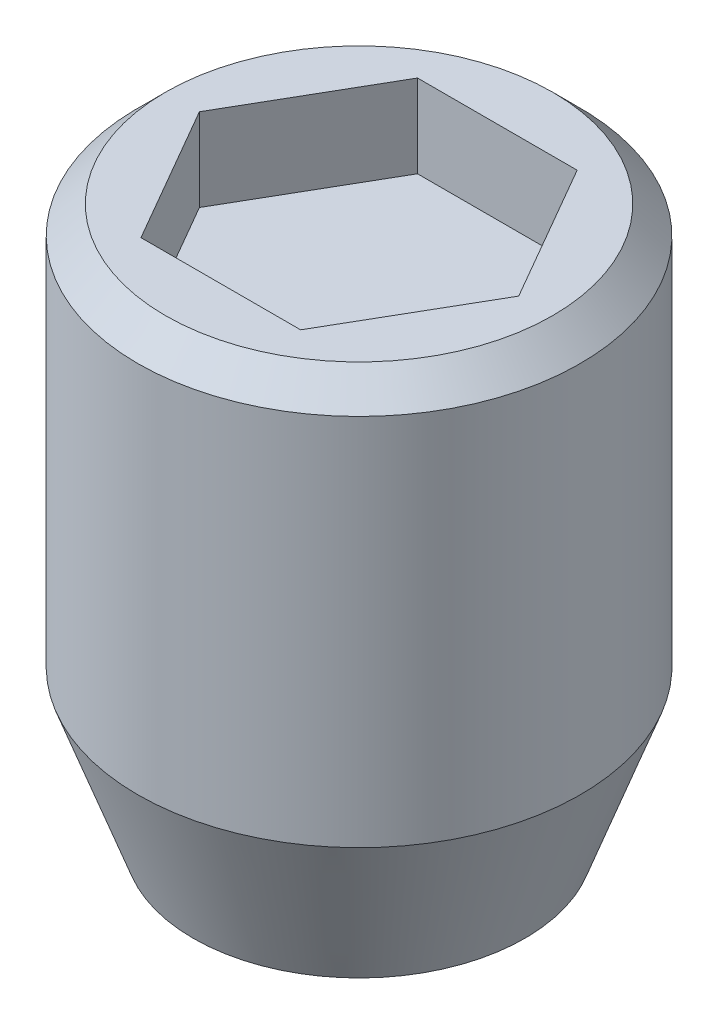
SolidWorks part; units mm, degrees
material "AISI 1020"
ref_plane "Front Plane" through (0, 0, 0) normal (0, 0, 1) x (1, 0, 0)
ref_plane "Top Plane" through (0, 0, 0) normal (0, 1, 0) x (1, 0, 0)
ref_plane "Right Plane" through (0, 0, 0) normal (1, 0, 0) x (0, 0, -1)
sketch "Sketch2" plane through (0, 0, 0) normal (0, 1, 0) x (1, 0, 0)
  circle A0 centre (0, 0) radius 4
  dimension "D1" = 8
extrude "Boss-Extrude1" add sketch "Sketch2" along normal blind 10
sketch "Sketch3" plane through (0, 10, 0) normal (0, 1, 0) x (1, 0, 0)
  line L1 (2.8868, 0) -> (1.4434, 2.5)
  line L2 (1.4434, 2.5) -> (-1.4434, 2.5)
  line L3 (-1.4434, 2.5) -> (-2.8868, 0)
  line L4 (-2.8868, 0) -> (-1.4434, -2.5)
  line L5 (-1.4434, -2.5) -> (1.4434, -2.5)
  line L6 (1.4434, -2.5) -> (2.8868, 0)
  circle A1 centre (0, 0) radius 2.5 construction
  circle A2 centre (0, 0) radius 2.5
  circle A3 centre (0, 0) radius 2.5 construction
  dimension "D1" = 1.5
extrude "Cut-Extrude1" cut sketch "Sketch3" against normal blind 1.5
chamfer "Chamfer1" distance 0.5 angle 45 1 edges at (0, 10, 4)
chamfer "Chamfer2" distance 1 angle 70 1 edges at (0, 0, 4)
